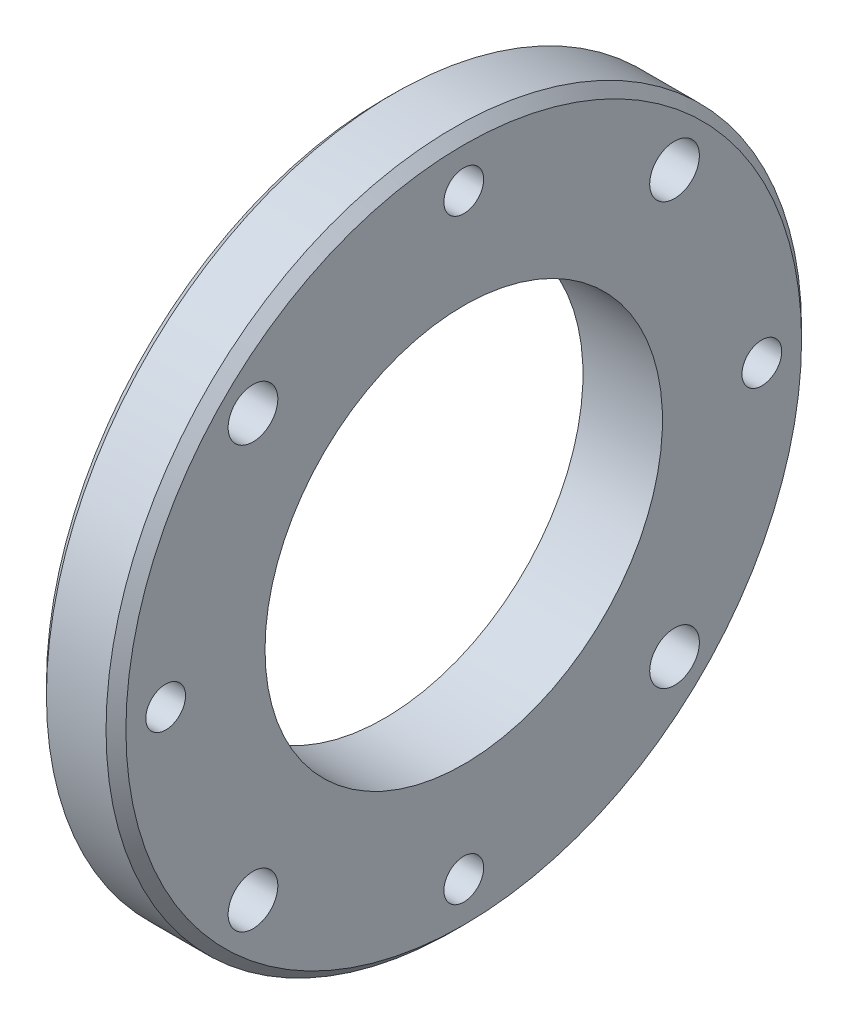
SolidWorks part; units mm, degrees
ref_plane "Plan1" through (0, 0, 0) normal (0, 0, 1) x (1, 0, 0)
ref_plane "Plan2" through (0, 0, 0) normal (0, 1, 0) x (1, 0, 0)
ref_plane "Plan3" through (0, 0, 0) normal (1, 0, 0) x (0, 0, -1)
sketch "Esquisse1" plane through (0, 0, 0) normal (0, 0, 1) x (1, 0, 0)
  line L0 (0, 35) -> (0, 20)
  line L1 (0, 20) -> (8, 20)
  line L2 (8, 20) -> (8, 35)
  line L5 (8, 35) -> (0, 35)
  line L6 (0, 0) -> (55, 0) construction
  dimension "D1" = 35
  dimension "D3" = 8
  dimension "D4" = 20
revolve "Base-Révolution" add sketch "Esquisse1" angle 360 about L6
chamfer "Chanfrein1" distance 1 angle 45
sketch "Esquisse3" plane through (0, 0, 0) normal (-1, 0, 0) x (0, 0, 1)
  line L0 (0, 0) -> (0, 30) construction
  line L1 (0, 0) -> (21.2132, 21.2132) construction
  circle A0 centre (0, 30) radius 2
  circle A12 centre (21.2132, 21.2132) radius 2.5
  circle A14 centre (30, 0) radius 2
  circle A15 centre (21.2132, -21.2132) radius 2.5
  circle A16 centre (0, -30) radius 2
  circle A17 centre (-21.2132, -21.2132) radius 2.5
  circle A18 centre (-30, 0) radius 2
  circle A19 centre (-21.2132, 21.2132) radius 2.5
  dimension "D1" = 4
  dimension "D4" = 30
  dimension "D2" = 5
  dimension "D3" = 45
  dimension "D5" = 30
extrude "Enlèv. mat.-Extru.2" cut sketch "Esquisse3" against normal through all
